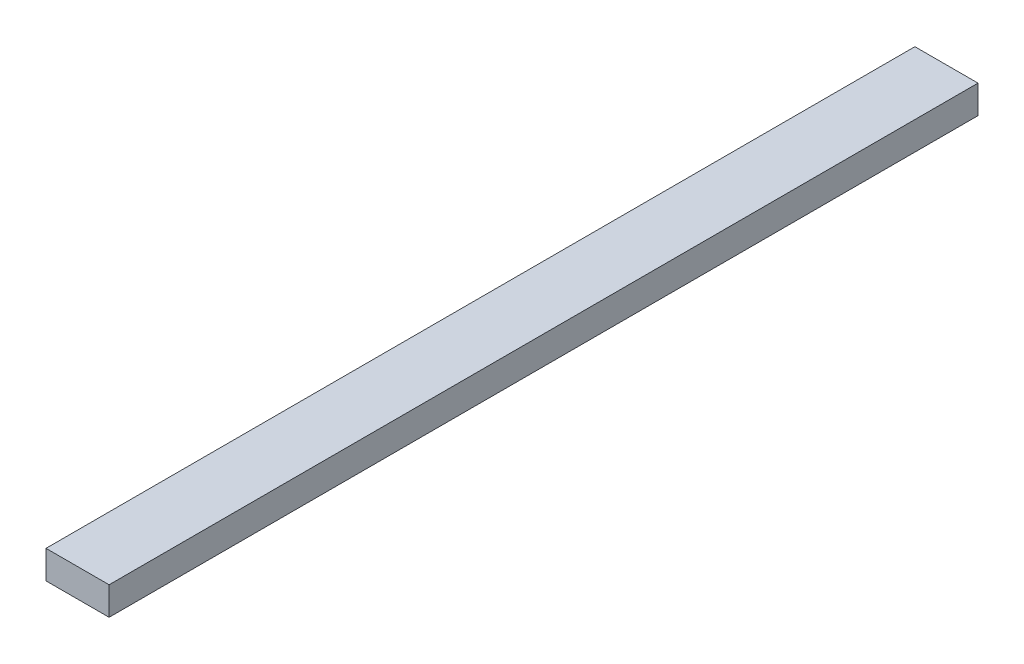
SolidWorks part; units mm, degrees
ref_plane "Front Plane" through (0, 0, 0) normal (1, 0, 0) x (0, 1, 0)
ref_plane "Top Plane" through (0, 0, 0) normal (0, 0, 1) x (0, 1, 0)
ref_plane "Right Plane" through (0, 0, 0) normal (0, 1, 0) x (-1, 0, 0)
sketch "Sketch1" plane through (0, 0, 0) normal (0, 0, 1) x (0, 1, 0)
  line L1 (-8.3312, -18.6436) -> (8.3312, -18.6436)
  line L2 (-8.3312, -18.6436) -> (-8.3312, 18.6436)
  line L3 (-8.3312, 18.6436) -> (8.3312, 18.6436)
  line L4 (8.3312, -18.6436) -> (8.3312, 18.6436)
  line L5 (-8.3312, -18.6436) -> (8.3312, 18.6436) construction
  line L6 (-8.3312, 18.6436) -> (8.3312, -18.6436) construction
  point P0 (0, 0)
  dimension "D1" = 16.6624
  dimension "D2" = 37.2872
extrude "Boss-Extrude1" add sketch "Sketch1" along normal mid plane 513.34
